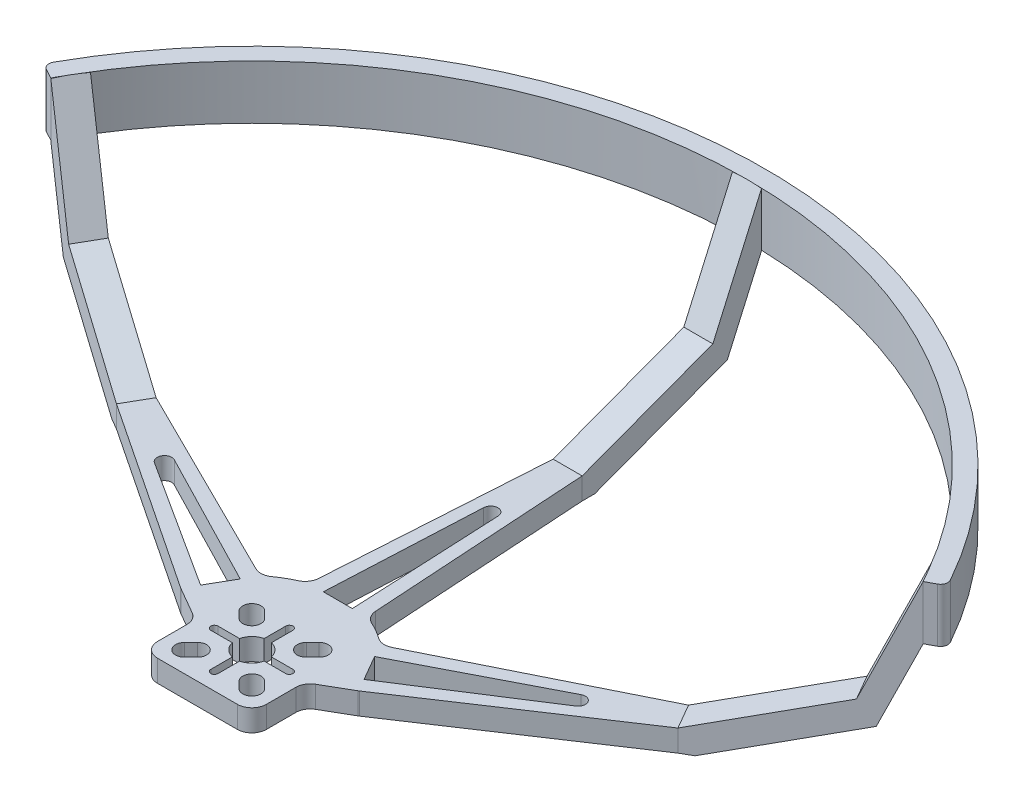
SolidWorks part; units mm, degrees
ref_plane "Front Plane" through (0, 0, 0) normal (0, 0, 1) x (1, 0, 0)
ref_plane "Top Plane" through (0, 0, 0) normal (0, 1, 0) x (1, 0, 0)
ref_plane "Right Plane" through (0, 0, 0) normal (1, 0, 0) x (0, 0, -1)
sketch "Sketch1" plane through (0, 0, 0) normal (0, 1, 0) x (1, 0, 0)
  line L0 (0, 0) -> (7.5, -7.5) construction
  line L1 (-7.5, -7.5) -> (7.5, -7.5)
  line L2 (-7.5, -7.5) -> (-7.5, 7.5)
  line L3 (-7.5, 7.5) -> (7.5, 7.5)
  line L4 (7.5, -7.5) -> (7.5, 7.5)
  line L5 (-7.5, -7.5) -> (7.5, 7.5) construction
  line L6 (-7.5, 7.5) -> (7.5, -7.5) construction
  line L7 (0, 0) -> (-7.5, -7.5) construction
  line L8 (0, 0) -> (7.5, 7.5) construction
  line L9 (-7.5, 7.5) -> (0, 0) construction
  line L10 (-7.5, 7.5) -> (0, 0) construction
  line L11 (7.5, 7.5) -> (0, 0) construction
  point P0 (0, 0)
  dimension "D1" = 15
  dimension "D2" = 15
extrude "Boss-Extrude1" add sketch "Sketch1" along normal blind 3
sketch "Sketch9" plane through (0, 0, 0) normal (1, 0, 0) x (0, 0, -1)
  line L0 (0, 0) -> (0, 7.495)
  line L1 (0, 13.4057) -> (0, -13.4057) construction
sketch "Sketch7" plane through (0, 0, -7.5) normal (0, 0, -1) x (-1, 0, 0)
  line L0 (0, 3) -> (0, 0) construction
  line L1 (-7.5, 3) -> (7.5, 3) construction
  line L3 (-4, 0) -> (4, 0)
  line L4 (-4, 0) -> (-4, 3)
  line L5 (-4, 3) -> (4, 3)
  line L6 (4, 0) -> (4, 3)
  line L7 (-4, 0) -> (4, 3) construction
  line L8 (-4, 3) -> (4, 0) construction
  point P5 (0, 1.5)
  dimension "D1" = 8
  dimension "D2" = 3
extrude "Boss-Extrude2" add sketch "Sketch7" along normal blind 5 and the other way blind 1.18
pattern_circular "CirPattern2" count 2 every 60 about axis through (0, 0, 0) along (0, 1, 0) of "Boss-Extrude2"
hole_wizard "Tap Drill for M3 Tap1" positions "Sketch6" profile "Sketch3" hole size "M3" standard "ISO" end condition through all
sketch "Sketch6" plane through (0, 3, 0) normal (0, 1, 0) x (1, 0, 0)
  line L0 (-7.5, 7.5) -> (0, 0) construction
  line L1 (0, 0) -> (7.5, -7.5) construction
  line L2 (7.5, 7.5) -> (0, 0) construction
  line L3 (0, 0) -> (-7.5, -7.5) construction
  line L4 (4.088, 7.5) -> (7.5, 7.5)
  line L5 (4.9904, 7.5) -> (4, 7.5) construction
  line L6 (-4.6859, 7.5) -> (-7.5, 7.5)
  line L7 (-4, 7.5) -> (-4.9904, 7.5) construction
  line L8 (7.5, -0.6771) -> (7.5, 7.5)
  line L9 (7.5, -7.5) -> (7.5, -0.2887) construction
  line L10 (-7.5, -7.5) -> (-7.5, 7.5)
  line L11 (-7.5, 7.5) -> (7.5, 7.5)
  point P21 (-3.75, 3.75)
  point P23 (3.75, -3.75)
  point P34 (3.75, 3.75)
  point P36 (-3.75, -3.75)
sketch "Sketch3" plane through (-3.75, 3, 3.75) normal (1, 0, 0) x (0, 0, 1)
  line L0 (0, 0) -> (0, 3)
  line L1 (0, 3) -> (1.25, 3)
  line L2 (1.25, 3) -> (1.25, 0)
  line L5 (1.25, 0) -> (0, 0)
  line L11 (0, -6.35) -> (0, 107.95) construction
  dimension "Thru Hole Dia." = 2.5
  dimension "Thru Hole Depth" = 3
sketch "Sketch10" plane through (0, 3, 0) normal (0, 1, 0) x (1, 0, 0)
  line L1 (0, 0) -> (7.5, -0.2887)
  line L4 (7.5, -0.2887) -> (13.3196, -0.5127)
  line L6 (0, 0) -> (-7.5, -0.2887)
  line L7 (-7.5, -0.2887) -> (-10.3284, -0.3975)
  line L8 (-10.3284, -0.3975) -> (-14.5069, -0.5584)
  circle A4 centre (0, 0) radius 12.5
  circle A5 centre (0, 0) radius 7.5
extrude "Boss-Extrude4" add sketch "Sketch10" against normal up to surface (3 mm away)
sketch "Sketch21" plane through (0, 3, 0) normal (0, 1, 0) x (1, 0, 0)
  line L0 (-3.75, 3.75) -> (7.5, -7.5)
  line L1 (3.75, 3.75) -> (-7.5, -7.5)
  line L2 (0, 1.8925) -> (0, 2.25)
  line L4 (-5.1642, 5.1642) -> (5.1642, 5.1642)
  line L6 (-0.5, 5.1642) -> (-0.5, 2.1937)
  line L7 (0.5, 5.1642) -> (0.5, 2.1937)
  line L8 (5.1642, -0.5) -> (2.1937, -0.5)
  line L9 (5.1642, 0.5) -> (2.1937, 0.5)
  line L10 (0.5, -5.1642) -> (0.5, -2.1937)
  line L11 (-0.5, -5.1642) -> (-0.5, -2.1937)
  line L12 (-5.1642, -0.5) -> (-2.1937, -0.5)
  line L13 (-5.1642, 0.5) -> (-2.1937, 0.5)
  line L14 (-2.8661, 4.6339) -> (-3.75, 5.5178)
  line L15 (3.75, 3.75) -> (4.1531, 3.3469)
  line L16 (2.8661, 4.6339) -> (4.6339, 2.8661)
  line L17 (2.8661, 4.6339) -> (3.75, 5.5178)
  line L19 (5.5178, 3.75) -> (4.6339, 2.8661)
  line L20 (-2.8661, 4.6339) -> (-4.6339, 2.8661)
  line L21 (-5.5178, 3.75) -> (-4.6339, 2.8661)
  line L22 (-2.8661, -4.6339) -> (-4.6339, -2.8661)
  line L23 (-5.5178, -3.75) -> (-4.6339, -2.8661)
  line L24 (-2.8661, -4.6339) -> (-3.75, -5.5178)
  line L25 (2.8661, -4.6339) -> (3.75, -5.5178)
  line L26 (2.8661, -4.6339) -> (4.6339, -2.8661)
  line L27 (5.5178, -3.75) -> (4.6339, -2.8661)
  arc A0 (-2.1937, -0.5) -> (-0.5, -2.1937) centre (0, 0) ccw
  arc A1 (0.5, 5.1642) -> (-0.5, 5.1642) centre (0, 5.1642) ccw
  circle A2 centre (5.1642, 0) radius 0.5
  arc A3 (-0.5, -5.1642) -> (0.5, -5.1642) centre (0, -5.1642) ccw
  arc A4 (-5.1642, -0.5) -> (-5.1642, 0.5) centre (-5.1642, 0) cw
  circle A5 centre (3.75, 3.75) radius 1.25 construction
  arc A7 (5.5178, 3.75) -> (3.75, 5.5178) centre (4.6339, 4.6339) ccw
  arc A8 (-5.5178, 3.75) -> (-3.75, 5.5178) centre (-4.6339, 4.6339) cw
  arc A9 (-5.5178, -3.75) -> (-3.75, -5.5178) centre (-4.6339, -4.6339) ccw
  arc A10 (5.5178, -3.75) -> (3.75, -5.5178) centre (4.6339, -4.6339) cw
  arc A11 (-0.5, 2.1937) -> (-2.1937, 0.5) centre (0, 0) ccw
  arc A12 (2.1937, 0.5) -> (0.5, 2.1937) centre (0, 0) ccw
  arc A13 (0.5, -2.1937) -> (2.1937, -0.5) centre (0, 0) ccw
  point P21 (3.75, 3.75)
extrude "Cut-Extrude1" cut sketch "Sketch21" against normal blind 10
fillet "Fillet12" radius 2 2 edges at (-7.5, 1.5, 7.5) (7.5, 1.5, 7.5)
sketch "Sketch22" plane through (0, 0, 0) normal (1, 0, 0) x (0, 0, -1)
  line L0 (12.5, 3) -> (43.5, 3)
  line L1 (12.5, 0) -> (43.5, 0)
  line L2 (11, 0) -> (-11, 0) construction
  line L3 (12.5, 3) -> (12.5, 0) construction
  line L4 (43.5, 0) -> (43.5, 3)
  line L5 (12.5, 3) -> (12.5, 0)
  dimension "D1" = 31
extrude "Boss-Extrude11" add sketch "Sketch22" along normal blind 4 and the other way blind 4
pattern_circular "CirPattern8" count 2 every 60 about axis through (0, 0, 0) along (0, 1, 0) of "Boss-Extrude11"
sketch "Sketch23" plane through (0, 3, 0) normal (0, 1, 0) x (1, 0, 0)
  line L0 (-4, 11.8427) -> (0, 11.8427) construction
  line L1 (0, -4.1223) -> (0, 4.1223) construction
  line L2 (0, 11.8427) -> (4, 11.8427) construction
  line L3 (2, 11.8427) -> (0.3543, 20.0712)
  line L4 (-0.3543, 20.0712) -> (-2, 11.8427)
  line L5 (-2, 11.8427) -> (2, 11.8427)
  line L6 (4, 11.8427) -> (2, 20.0712)
  line L7 (2, 20.0712) -> (2, 43.5)
  line L8 (-4, 43.5) -> (4, 43.5) construction
  line L9 (2, 43.5) -> (-2, 43.5)
  line L10 (-2, 43.5) -> (-2, 20.0712)
  line L11 (-2, 20.0712) -> (-4, 11.8427)
  line L12 (-4, 11.8427) -> (4, 11.8427)
  line L22 (0, 11.8427) -> (0, 20.0003)
  line L32 (2, 11.8427) -> (0, 11.8427) construction
  line L33 (0, 11.8427) -> (-2, 11.8427) construction
  line L34 (1, 32.8981) -> (2, 11.8427)
  line L35 (-1, 32.8981) -> (-2, 11.8427)
  line L36 (4, 11.8427) -> (2, 43.5)
  line L37 (-2, 43.5) -> (-4, 11.8427)
  line L38 (8.2561, 9.3855) -> (12.2561, 2.4573)
  line L39 (12.2561, 2.4573) -> (18.3822, 8.3035)
  line L40 (18.3822, 8.3035) -> (38.6721, 20.0179)
  line L41 (38.6721, 20.0179) -> (36.6721, 23.4821)
  line L42 (36.6721, 23.4821) -> (16.3822, 11.7676)
  line L43 (16.3822, 11.7676) -> (8.2561, 9.3855)
  line L44 (27.9906, 17.3151) -> (9.2561, 7.6534)
  line L45 (28.9906, 15.583) -> (11.2561, 4.1893)
  line L46 (-28.9906, 15.583) -> (-11.2561, 4.1893)
  line L47 (-27.9906, 17.3151) -> (-9.2561, 7.6534)
  line L48 (-16.3822, 11.7676) -> (-8.2561, 9.3855)
  line L49 (-36.6721, 23.4821) -> (-16.3822, 11.7676)
  line L50 (-38.6721, 20.0179) -> (-36.6721, 23.4821)
  line L51 (-18.3822, 8.3035) -> (-38.6721, 20.0179)
  line L52 (-12.2561, 2.4573) -> (-18.3822, 8.3035)
  line L53 (-8.2561, 9.3855) -> (-12.2561, 2.4573)
  line L54 (8.2561, 9.3855) -> (36.6721, 23.4821)
  line L55 (38.6721, 20.0179) -> (12.2561, 2.4573)
  line L56 (-8.2561, 9.3855) -> (-36.6721, 23.4821)
  line L57 (-38.6721, 20.0179) -> (-12.2561, 2.4573)
  arc A0 (0.3543, 20.0712) -> (-0.3543, 20.0712) centre (0, 20.0003) ccw
  arc A3 (1, 32.8981) -> (-1, 32.8981) centre (0, 32.8981) ccw
  arc A4 (28.9906, 15.583) -> (27.9906, 17.3151) centre (28.4906, 16.4491) ccw
  arc A5 (-28.9906, 15.583) -> (-27.9906, 17.3151) centre (-28.4906, 16.4491) cw
  point P32 (0, 0)
  point P33 (0, 0)
  dimension "D1" = 8.1576
  dimension "D2" = 2
extrude "Cut-Extrude2" cut sketch "Sketch23" against normal blind 15
fillet "Fillet13" radius 2 8 edges at (4, 1.5, -11.8427) (8.2561, 1.5, -9.3855) (12.2561, 1.5, -2.4573) (-12.2561, 1.5, -2.4573) (7.5, 1.5, 0.2887) (-7.5, 1.5, 0.2887) (-8.2561, 1.5, -9.3855) (-4, 1.5, -11.8427)
sketch "Sketch24" plane through (0, 0, 0) normal (1, 0, 0) x (0, 0, -1)
  line L0 (43.5, 3) -> (61.5, 9.75)
  line L1 (28.05, 0) -> (-28.05, 0) construction
  line L4 (61.5, 9.75) -> (68.2334, 25)
  line L5 (63.4988, 6.8495) -> (68.2334, 17.5726)
  line L6 (45.2334, 0) -> (63.4988, 6.8495)
  line L7 (45.2334, 0) -> (43.5, 0)
  line L8 (43.5, 3) -> (43.5, 0)
  line L9 (68.2334, 25) -> (68.2334, 17.5726)
  line L10 (45.2334, 0) -> (43.5, 0)
  line L11 (43.5, 3) -> (43.5, 0)
  dimension "D1" = 18
  dimension "D2" = 23
  dimension "D3" = 3
extrude "Boss-Extrude12" add sketch "Sketch24" against normal blind 2 and the other way blind 2 contours L9 L4 L0 L8 L7 L6 L5
pattern_circular "CirPattern9" count 2 every 60 about axis through (0, 0, 0) along (0, 1, 0) of "Boss-Extrude12"
sketch "Sketch25" plane through (0, 0, 0) normal (1, 0, 0) x (0, 0, -1)
  line L0 (68.2334, 25) -> (70.7334, 25)
  line L1 (68.2334, 25) -> (68.2334, 17.5726)
  line L2 (68.2334, 17.5726) -> (70.7334, 17.5726)
  line L3 (70.7334, 17.5726) -> (70.7334, 25)
  line L4 (0, 0) -> (0, 7.495)
  dimension "D1" = 2.5
revolve "Revolve1" add sketch "Sketch25" angle 61.68 about L4 other way angle 61.68
fillet "Fillet14" radius 1 2 edges at (-62.2674, 21.2863, -33.5556) (62.2674, 21.2863, -33.5556)
